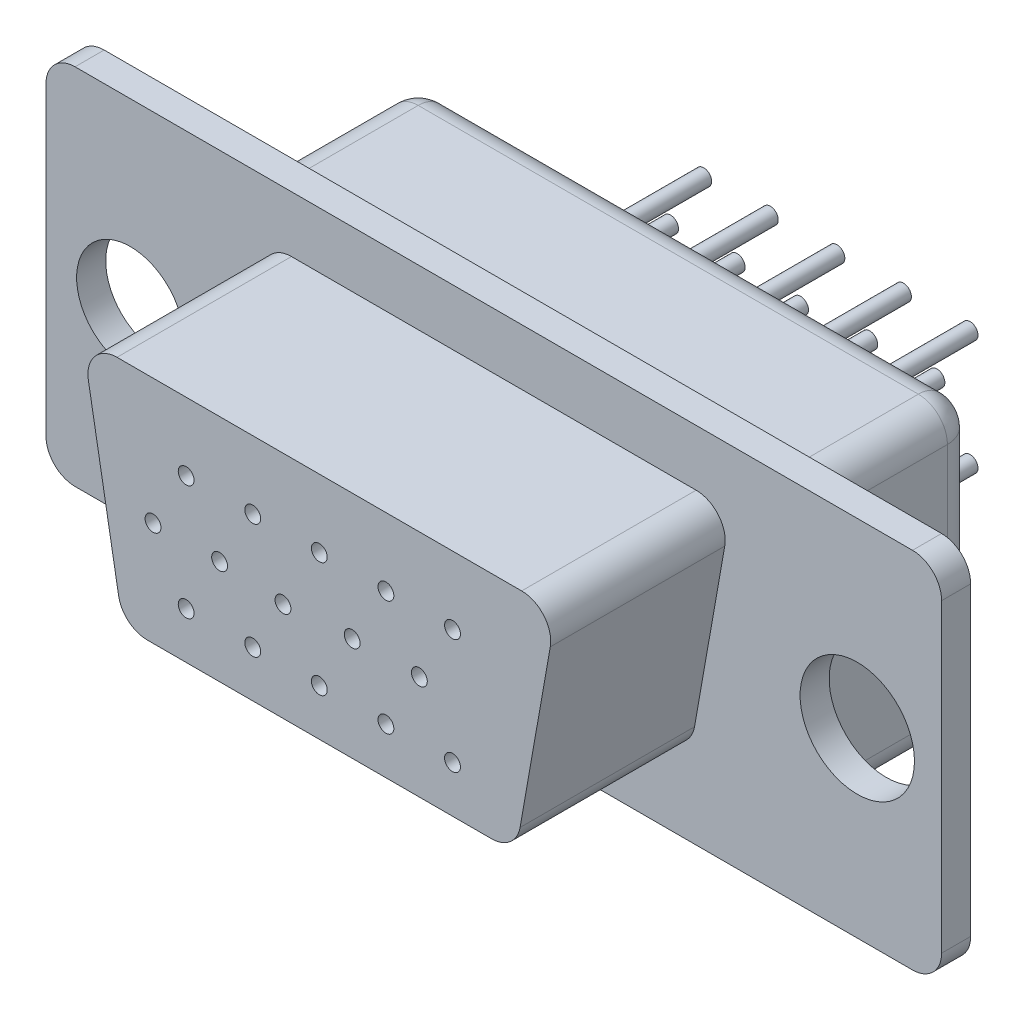
SolidWorks part; units mm, degrees
ref_plane "Plan de face" through (0, 0, 0) normal (0, 0, 1) x (1, 0, 0)
ref_plane "Plan de dessus" through (0, 0, 0) normal (0, 1, 0) x (1, 0, 0)
ref_plane "Plan de droite" through (0, 0, 0) normal (1, 0, 0) x (0, 0, -1)
sketch "Esquisse1" plane through (0, 0, 0) normal (0, 0, 1) x (1, 0, 0)
  line L0 (0, 0) -> (30.8, 12.5) construction
  line L1 (0, 0) -> (30.8, 0)
  line L2 (0, 0) -> (0, 12.5)
  line L3 (0, 12.5) -> (30.8, 12.5)
  line L4 (30.8, 0) -> (30.8, 12.5)
  line L5 (27.9, 6.25) -> (2.9, 6.25) construction
  line L6 (0, 12.5) -> (30.8, 0) construction
  circle A0 centre (2.9, 6.25) radius 1.8473
  circle A1 centre (27.9, 6.25) radius 1.9669
  point P9 (15.4, 6.25)
  dimension "D1" = 30.8
  dimension "D2" = 12.5
  dimension "D3" = 25
extrude "Extrusion1" add sketch "Esquisse1" along normal blind 1
sketch "Esquisse2" plane through (0, 0, 1) normal (0, 0, 1) x (1, 0, 0)
  line L0 (8.4418, 10.5691) -> (22.3582, 10.5691)
  line L1 (23.3431, 9.3955) -> (22.3027, 3.4955)
  line L2 (21.3179, 2.6691) -> (9.4821, 2.6691)
  line L3 (8.4973, 3.4955) -> (7.4569, 9.3955)
  line L4 (0, 0) -> (30.8, 12.5) construction
  line L5 (30.8, 0) -> (30.8, 12.5) construction
  line L6 (0, 12.5) -> (30.8, 0) construction
  line L7 (7.25, 10.5691) -> (22.157, 2.6691) construction
  line L8 (23.55, 10.5691) -> (8.643, 2.6691) construction
  arc A0 (7.4569, 9.3955) -> (8.4418, 10.5691) centre (8.4418, 9.5691) cw
  arc A3 (23.3431, 9.3955) -> (22.3582, 10.5691) centre (22.3582, 9.5691) ccw
  arc A4 (22.3027, 3.4955) -> (21.3179, 2.6691) centre (21.3179, 3.6691) cw
  arc A6 (9.4821, 2.6691) -> (8.4973, 3.4955) centre (9.4821, 3.6691) cw
  point P13 (15.4, 6.25)
  point P14 (15.4, 6.25)
  dimension "D9" = 1
  dimension "D1" = 16.3
  dimension "D2" = 100
  dimension "D3" = 100
  dimension "D4" = 7.9
extrude "Extrusion2" add sketch "Esquisse2" along normal blind 6
sketch "Esquisse3" plane through (0, 0, 0) normal (0, 0, -1) x (-1, 0, 0)
  line L0 (-25, 1.25) -> (-5.8, 11.25) construction
  line L1 (-25, 11.25) -> (-5.8, 11.25)
  line L2 (-25, 11.25) -> (-25, 1.25)
  line L3 (-25, 1.25) -> (-5.8, 1.25)
  line L4 (-5.8, 11.25) -> (-5.8, 1.25)
  line L5 (-5.8, 1.25) -> (-25, 11.25) construction
  line L6 (-30.8, 12.5) -> (0, 0) construction
  line L8 (0, 12.5) -> (-30.8, 0) construction
  point P8 (-15.4, 6.25)
  point P13 (-15.4, 6.25)
  dimension "D1" = 19.2
  dimension "D2" = 10
extrude "Extrusion3" add sketch "Esquisse3" along normal blind 6
sketch "Esquisse4" plane through (0, 0, -6) normal (0, 0, -1) x (-1, 0, 0)
  line L0 (-19.98, 8.23) -> (-10.82, 8.23) construction
  line L1 (-10.82, 8.23) -> (-9.544, 6.0138) construction
  line L2 (-10.82, 4.27) -> (-19.98, 4.27) construction
  line L3 (-19.98, 8.23) -> (-19.98, 4.27) construction
  line L4 (-17.69, 8.23) -> (-16.3999, 5.9892) construction
  line L5 (-15.4, 8.23) -> (-14.0179, 5.8295) construction
  line L6 (-13.11, 8.23) -> (-11.834, 6.0138) construction
  line L7 (-18.84, 6.25) -> (-9.68, 6.25) construction
  line L8 (-18.84, 6.25) -> (-19.98, 8.23) construction
  line L9 (-17.69, 4.27) -> (-17.69, 8.23) construction
  line L10 (-15.4, 8.23) -> (-15.4, 4.27) construction
  line L11 (-13.11, 8.23) -> (-13.11, 4.27) construction
  line L12 (-10.82, 4.27) -> (-10.82, 8.23) construction
  line L13 (-25, 1.25) -> (-5.8, 11.25) construction
  line L14 (-25, 11.25) -> (-5.8, 1.25) construction
  circle A0 centre (-19.98, 8.23) radius 0.2725
  circle A1 centre (-17.69, 8.23) radius 0.2725
  circle A2 centre (-15.4, 8.23) radius 0.2725
  circle A3 centre (-13.11, 8.23) radius 0.2725
  circle A4 centre (-10.82, 8.23) radius 0.2725
  circle A5 centre (-9.68, 6.25) radius 0.2725
  circle A6 centre (-11.97, 6.25) radius 0.2725
  circle A7 centre (-14.1497, 6.0681) radius 0.2725
  circle A8 centre (-16.5297, 6.2288) radius 0.2725
  circle A9 centre (-18.84, 6.25) radius 0.2725
  circle A10 centre (-19.98, 4.27) radius 0.2725
  circle A11 centre (-17.69, 4.27) radius 0.2725
  circle A12 centre (-15.4, 4.27) radius 0.2725
  circle A13 centre (-13.11, 4.27) radius 0.2725
  circle A14 centre (-10.82, 4.27) radius 0.2725
  point P13 (-16.55, 6.25)
  point P14 (-14.26, 6.25)
  point P15 (-11.97, 6.25)
  point P39 (-15.4, 6.25)
  dimension "D1" = 2.29
  dimension "D2" = 2.29
  dimension "D3" = 2.29
  dimension "D4" = 2.29
  dimension "D5" = 1.98
  dimension "D6" = 1.98
  dimension "D7" = 1.14
extrude "Extrusion4" add sketch "Esquisse4" along normal blind 4.8
fillet "Congé1" radius 1 12 edges at (15.4, 1.25, -6) (5.8, 6.25, -6) (5.8, 1.25, -3) (5.8, 11.25, -3) (15.4, 11.25, -6) (25, 11.25, -3) (25, 6.25, -6) (25, 1.25, -3) (30.8, 0, 0.5) (30.8, 12.5, 0.5) (0, 0, 0.5) (0, 12.5, 0.5)
sketch "Esquisse7" plane through (0, 0, 1) normal (0, 0, 1) x (1, 0, 0)
  circle A0 centre (19.98, 8.23) radius 0.2725
  circle A1 centre (17.69, 8.23) radius 0.2725
  circle A2 centre (15.4, 8.23) radius 0.2725
  circle A3 centre (13.11, 8.23) radius 0.2725
  circle A4 centre (10.82, 8.23) radius 0.2725
  circle A5 centre (9.68, 6.25) radius 0.2725
  circle A6 centre (11.97, 6.25) radius 0.2725
  circle A7 centre (14.1497, 6.0681) radius 0.2725
  circle A8 centre (16.5297, 6.2288) radius 0.2725
  circle A9 centre (18.84, 6.25) radius 0.2725
  circle A10 centre (19.98, 4.27) radius 0.2725
  circle A11 centre (17.69, 4.27) radius 0.2725
  circle A12 centre (15.4, 4.27) radius 0.2725
  circle A13 centre (13.11, 4.27) radius 0.2725
  circle A14 centre (10.82, 4.27) radius 0.2725
extrude "Extrusion5" cut sketch "Esquisse7" along normal up to surface (6 mm away) up to face at (15.4, 6.5449, 7)
